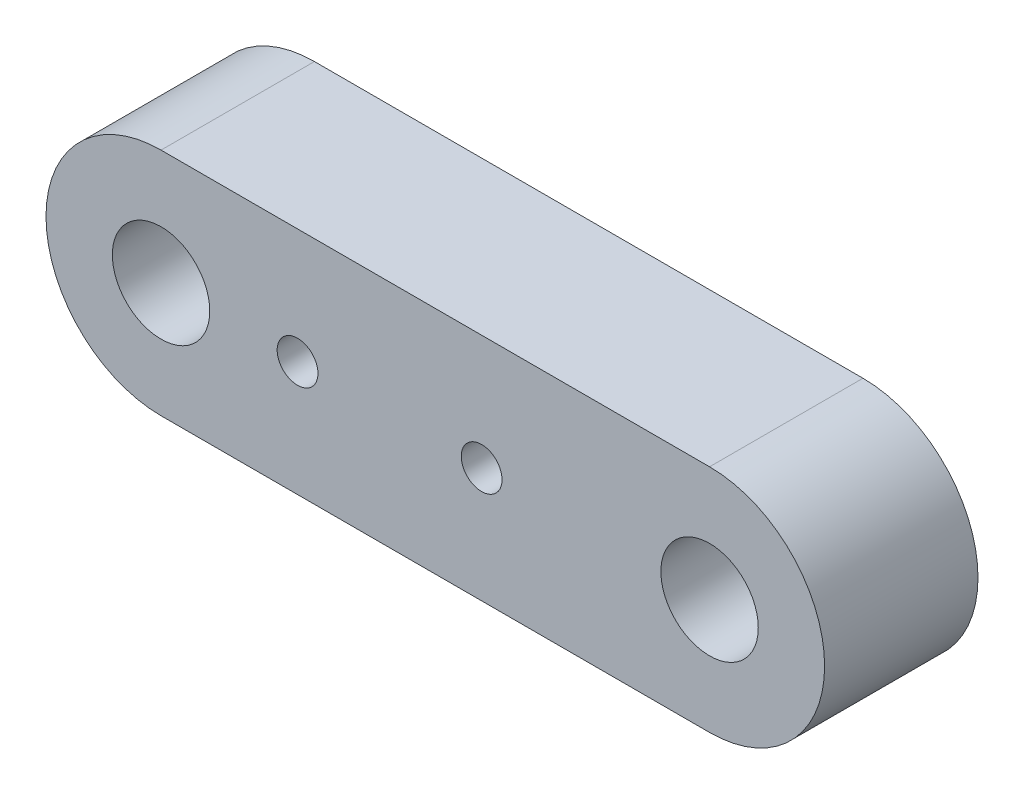
SolidWorks part; units mm, degrees
ref_plane "Front Plane" through (0, 0, 0) normal (0, 0, 1) x (1, 0, 0)
ref_plane "Top Plane" through (0, 0, 0) normal (0, 1, 0) x (1, 0, 0)
ref_plane "Right Plane" through (0, 0, 0) normal (1, 0, 0) x (0, 0, -1)
sketch "Sketch1" plane through (0, 0, 0) normal (0, 0, 1) x (1, 0, 0)
  line L0 (-8.94, 0) -> (8.94, 0) construction
  line L1 (-8.94, 3.75) -> (8.94, 3.75)
  line L2 (-8.94, -3.75) -> (8.94, -3.75)
  arc A0 (-8.94, 3.75) -> (-8.94, -3.75) centre (-8.94, 0) ccw
  arc A1 (8.94, -3.75) -> (8.94, 3.75) centre (8.94, 0) ccw
  point P3 (0, 0)
  dimension "D1" = 17.88
  dimension "D2" = 7.5
extrude "Boss-Extrude1" add sketch "Sketch1" along normal mid plane 5
sketch "Sketch2" plane through (0, 0, 2.5) normal (0, 0, 1) x (1, 0, 0)
  circle A0 centre (-8.94, 0) radius 1.5875
  circle A1 centre (8.94, 0) radius 1.5875
  arc A2 (8.94, -3.75) -> (8.94, 3.75) centre (8.94, 0) ccw construction
  arc A3 (-8.94, 3.75) -> (-8.94, -3.75) centre (-8.94, 0) ccw construction
  dimension "D1" = 3.175
extrude "Cut-Extrude1" cut sketch "Sketch2" against normal through all
sketch "Sketch5" plane through (0, 0, 2.5) normal (0, 0, 1) x (1, 0, 0)
  line L0 (-8.94, 0) -> (8.94, 0) construction
  circle A0 centre (-4.49, 0) radius 0.665
  circle A1 centre (1.51, 0) radius 0.665
  dimension "D1" = 1.33
  dimension "D2" = 4.45
  dimension "D3" = 6
extrude "Cut-Extrude2" cut sketch "Sketch5" against normal up to next
